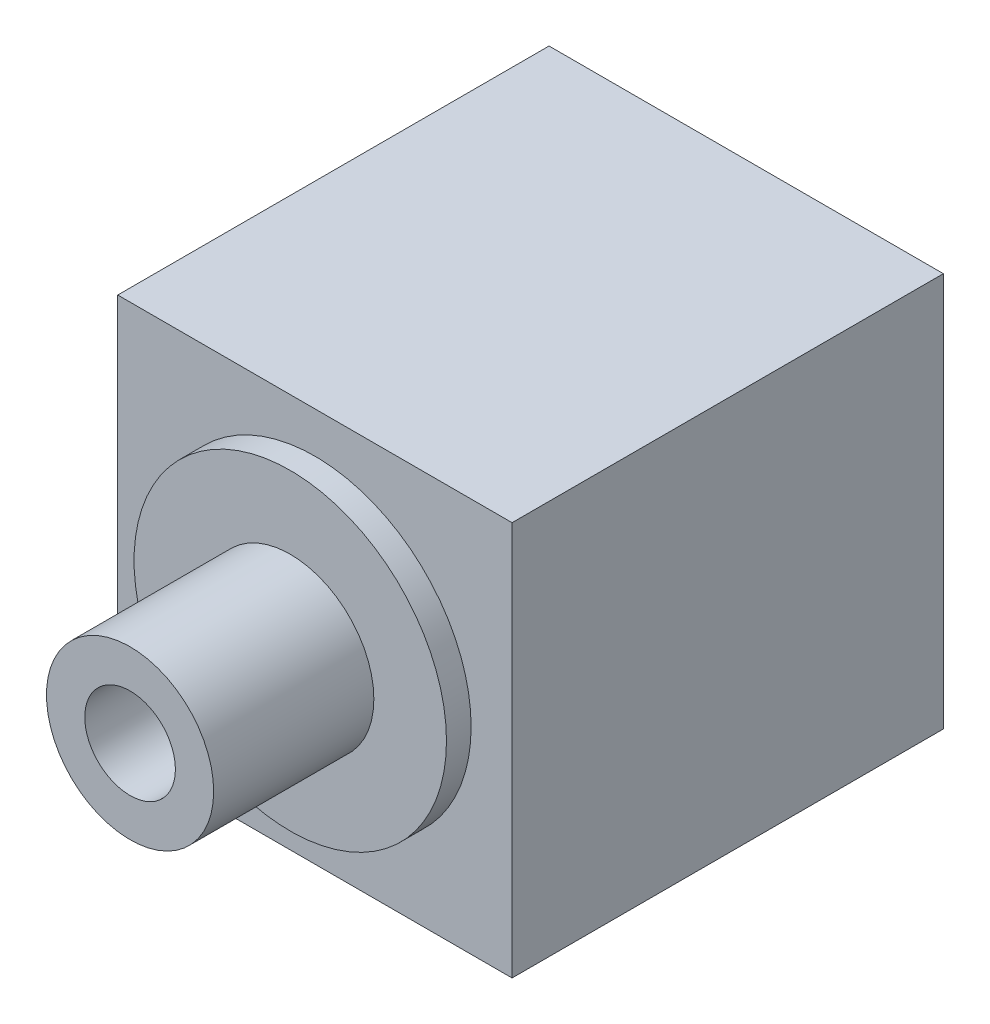
SolidWorks part; units mm, degrees
material "PE faible/moyenne densité"
ref_plane "Plan de face" through (0, 0, 0) normal (0, 0, 1) x (1, 0, 0)
ref_plane "Plan de dessus" through (0, 0, 0) normal (0, 1, 0) x (1, 0, 0)
ref_plane "Plan de droite" through (0, 0, 0) normal (1, 0, 0) x (0, 0, -1)
sketch "Esquisse1" plane through (0, 0, 0) normal (0, 0, 1) x (1, 0, 0)
  line L0 (0, 32.4706) -> (0, -35.6078) construction
  line L1 (-16, 16) -> (16, 16)
  line L2 (-16, 16) -> (-16, -16)
  line L3 (-16, -16) -> (16, -16)
  line L4 (16, 16) -> (16, -16)
  line L5 (-58.0466, 0) -> (53.6397, 0) construction
  dimension "D1" = 32
  dimension "D2" = 32
extrude "Boss.-Extru.1" add sketch "Esquisse1" along normal blind 35
sketch "Esquisse2" plane through (0, 0, 35) normal (0, 0, 1) x (1, 0, 0)
  circle A0 centre (0, 0) radius 6.784
  circle A1 centre (0, 0) radius 3.6779
extrude "Boss.-Extru.2" add sketch "Esquisse2" along normal blind 15
sketch "Esquisse3" plane through (0, 0, 35) normal (0, 0, 1) x (1, 0, 0)
  circle A0 centre (0, 0) radius 12.6767
extrude "Boss.-Extru.3" add sketch "Esquisse3" along normal blind 2
